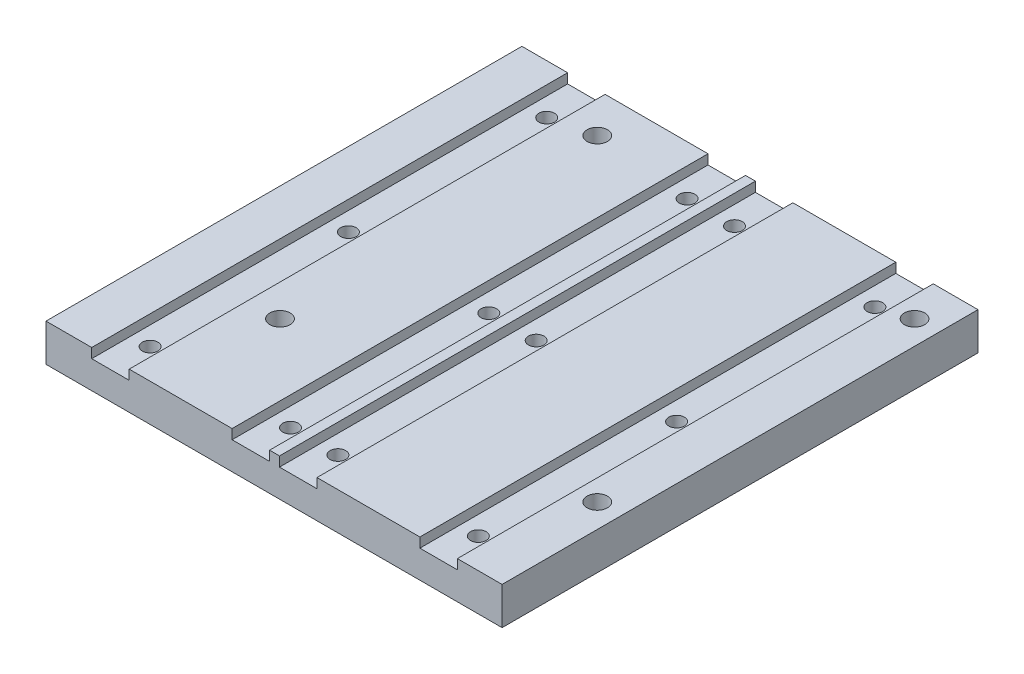
SolidWorks part; units mm, degrees
ref_plane "Front Plane" through (0, 0, 0) normal (0, 0, 1) x (1, 0, 0)
ref_plane "Top Plane" through (0, 0, 0) normal (0, 1, 0) x (1, 0, 0)
ref_plane "Right Plane" through (0, 0, 0) normal (1, 0, 0) x (0, 0, -1)
sketch "Sketch1" plane through (0, 0, 0) normal (0, 1, 0) x (1, 0, 0)
  line L1 (73.025, 76.2) -> (-73.025, 76.2)
  line L2 (73.025, 76.2) -> (73.025, -76.2)
  line L3 (73.025, -76.2) -> (-73.025, -76.2)
  line L4 (-73.025, 76.2) -> (-73.025, -76.2)
  line L5 (73.025, 76.2) -> (-73.025, -76.2) construction
  line L6 (73.025, -76.2) -> (-73.025, 76.2) construction
  line L7 (-36.195, 63.5) -> (65.405, 63.5) construction
  line L8 (-36.195, 63.5) -> (-36.195, -38.1) construction
  line L9 (-36.195, -38.1) -> (65.405, -38.1) construction
  line L10 (65.405, 63.5) -> (65.405, -38.1) construction
  line L11 (-36.195, 63.5) -> (65.405, -38.1) construction
  line L12 (-36.195, -38.1) -> (65.405, 63.5) construction
  point P0 (0, 0)
  point P6 (14.605, 12.7)
  point P11 (85.5348, 53.8017)
  point P12 (13.2411, 0)
  point P13 (13.2411, 0)
  point P14 (0, 0)
  point P15 (0, 0)
  dimension "D1" = 152.4
  dimension "D2" = 146.05
  dimension "D3" = 101.6
  dimension "D4" = 7.62
  dimension "D5" = 12.7
extrude "Boss-Extrude1" add sketch "Sketch1" against normal blind 12
hole_wizard "1/4 Clearance Hole1" positions "Sketch2" profile "Sketch3" hole size "1/4" standard "ANSI Inch" end condition through all
sketch "Sketch2" plane through (0, 0, 0) normal (0, 1, 0) x (1, 0, 0)
  point P0 (-36.195, 63.5)
  point P3 (-36.195, -38.1)
  point P6 (65.405, -38.1)
  point P9 (65.405, 63.5)
sketch "Sketch3" plane through (-36.195, 0, -63.5) normal (1, 0, 0) x (0, 0, 1)
  line L0 (0, 0) -> (0, 12)
  line L1 (0, 12) -> (3.2639, 12)
  line L2 (3.2639, 12) -> (3.2639, 0)
  line L5 (3.2639, 0) -> (0, 0)
  line L11 (0, -6.35) -> (0, 107.95) construction
  dimension "Thru Hole Dia." = 6.5278
  dimension "Thru Hole Depth" = 12
sketch "Sketch4" plane through (0, 0, 76.2) normal (0, 0, 1) x (1, 0, 0)
  line L0 (-73.025, 0) -> (73.025, 0) construction
  line L1 (46.705, -3.11) -> (58.705, -3.11)
  line L2 (46.705, -3.11) -> (46.705, 0)
  line L3 (46.705, 0) -> (58.705, 0)
  line L4 (58.705, -3.11) -> (58.705, 0)
  line L5 (46.705, -3.11) -> (58.705, 0) construction
  line L6 (46.705, 0) -> (58.705, -3.11) construction
  line L7 (73.025, -12) -> (73.025, 0) construction
  line L8 (-73.025, -12) -> (73.025, -12) construction
  point P0 (52.705, -1.555)
  dimension "D1" = 8.89
  dimension "D2" = 12
  dimension "D3" = 20.32
extrude "Cut-Extrude1" cut sketch "Sketch4" against normal through all
sketch "Sketch6" plane through (0, -12, 0) normal (0, -1, 0) x (1, 0, 0)
  line L0 (52.705, 63.5) -> (52.705, -63.5) construction
  line L1 (46.705, 76.2) -> (58.705, 76.2) construction
  line L2 (73.025, 76.2) -> (73.025, -76.2) construction
  line L3 (46.705, -76.2) -> (-73.025, -76.2) construction
  point P5 (52.705, 76.2)
  point P8 (73.025, 0)
  point P10 (52.705, 0)
  dimension "D1" = 12.7
hole_wizard "CBORE for #10 Socket Head Cap Screw1" positions "Sketch9" profile "Sketch8" counterbore size "#10" standard "ANSI Inch" end condition through all
sketch "Sketch9" plane through (0, -12, 0) normal (0, -1, 0) x (-1, 0, 0)
  point P0 (-52.705, -63.5)
  point P3 (-52.705, 63.5)
  point P7 (-52.705, 0)
sketch "Sketch8" plane through (52.705, -12, 63.5) normal (1, 0, 0) x (0, 0, -1)
  line L0 (0, 0) -> (0, 12)
  line L1 (0, 12) -> (2.4892, 12)
  line L3 (2.4892, 12) -> (2.4892, 4.826)
  line L4 (2.4892, 4.826) -> (4.7625, 4.826)
  line L5 (4.7625, 4.826) -> (4.7625, 0)
  line L7 (4.7625, 0) -> (0, 0)
  line L11 (0, -6.35) -> (0, 107.95) construction
  dimension "Thru Hole Dia." = 4.9784
  dimension "Thru Hole Depth" = 12
  dimension "C'Bore Dia." = 9.525
  dimension "C'Bore Depth" = 4.826
pattern_linear "LPattern1" count 2 spacing 44.958 along (-1, 0, 0) count 2 spacing 60.133 along (-1, 0, 0) of "Cut-Extrude1", "CBORE for #10 Socket Head Cap Screw1"
